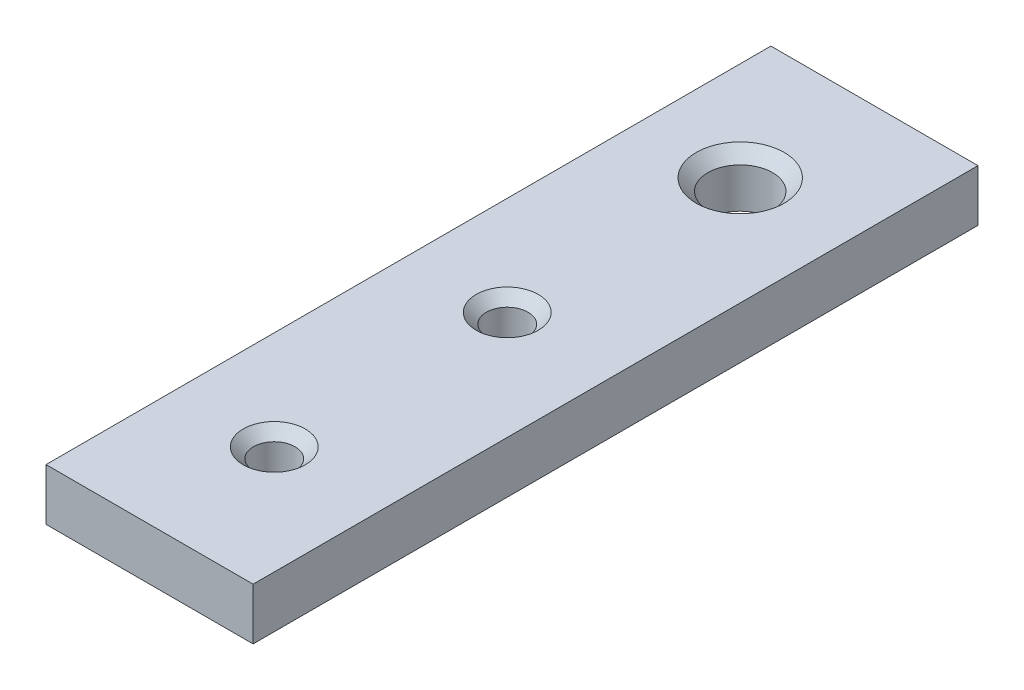
SolidWorks part; units mm, degrees
ref_plane "Front Plane" through (0, 0, 0) normal (0, 0, 1) x (1, 0, 0)
ref_plane "Top Plane" through (0, 0, 0) normal (0, 1, 0) x (1, 0, 0)
ref_plane "Right Plane" through (0, 0, 0) normal (1, 0, 0) x (0, 0, -1)
sketch "Sketch1" plane through (0, 0, 0) normal (0, 1, 0) x (1, 0, 0)
  line L1 (0, 0) -> (-25.4, 0)
  line L2 (0, 0) -> (0, 88.9)
  line L3 (0, 88.9) -> (-25.4, 88.9)
  line L4 (-25.4, 0) -> (-25.4, 88.9)
  dimension "D1" = 88.9
  dimension "D2" = 25.4
extrude "Boss-Extrude1" add sketch "Sketch1" along normal blind 6.35
hole_wizard "1/4-20 Tapped Hole1" positions "Sketch2" profile "Sketch3" tap size "1/4-20" standard "ANSI Inch" end condition through all
sketch "Sketch2" plane through (0, 6.35, 0) normal (0, 1, 0) x (1, 0, 0)
  line L0 (-25.4, 0) -> (0, 0) construction
  point P0 (-13.2844, 15.875)
  point P2 (-13.2844, 44.45)
  point P11 (0, 0)
  dimension "D1" = 15.875
  dimension "D3" = 44.45
sketch "Sketch3" plane through (-13.2844, 6.35, -15.875) normal (1, 0, 0) x (0, 0, 1)
  line L0 (0, 0) -> (0, 6.35)
  line L1 (0, 6.35) -> (2.5527, 6.35)
  line L2 (2.5527, 6.35) -> (2.5527, 1.2573)
  line L3 (2.5527, 1.2573) -> (3.81, 0)
  line L5 (3.81, 0) -> (0, 0)
  line L6 (-2.5527, 1.2573) -> (-3.81, 0) construction
  line L11 (0, -6.35) -> (0, 107.95) construction
  dimension "Thru Tap Drill Dia." = 5.1054
  dimension "Thru Tap Drill Depth" = 6.35
  dimension "Near C'Sink Dia." = 7.62
  dimension "Near C'Sink Angle" = 90
cosmetic thread "Hole Thread2"
cosmetic thread "Hole Thread3"
hole_wizard "3/8-16 Tapped Hole1" positions "Sketch4" profile "Sketch5" tap size "3/8-16" standard "ANSI Inch" end condition through all
sketch "Sketch4" plane through (0, 6.35, 0) normal (0, 1, 0) x (1, 0, 0)
  line L0 (0, 88.9) -> (-25.4, 88.9) construction
  point P0 (-13.2844, 73.025)
  dimension "D1" = 15.875
sketch "Sketch5" plane through (-13.2844, 6.35, -73.025) normal (1, 0, 0) x (0, 0, 1)
  line L0 (0, 0) -> (0, 6.35)
  line L1 (0, 6.35) -> (3.9687, 6.35)
  line L2 (3.9687, 6.35) -> (3.9687, 1.4287)
  line L3 (3.9687, 1.4287) -> (5.3975, 0)
  line L5 (5.3975, 0) -> (0, 0)
  line L6 (-3.9687, 1.4287) -> (-5.3975, 0) construction
  line L11 (0, -6.35) -> (0, 107.95) construction
  dimension "Thru Tap Drill Dia." = 7.9375
  dimension "Thru Tap Drill Depth" = 6.35
  dimension "Near C'Sink Dia." = 10.795
  dimension "Near C'Sink Angle" = 90
cosmetic thread "Hole Thread4"
